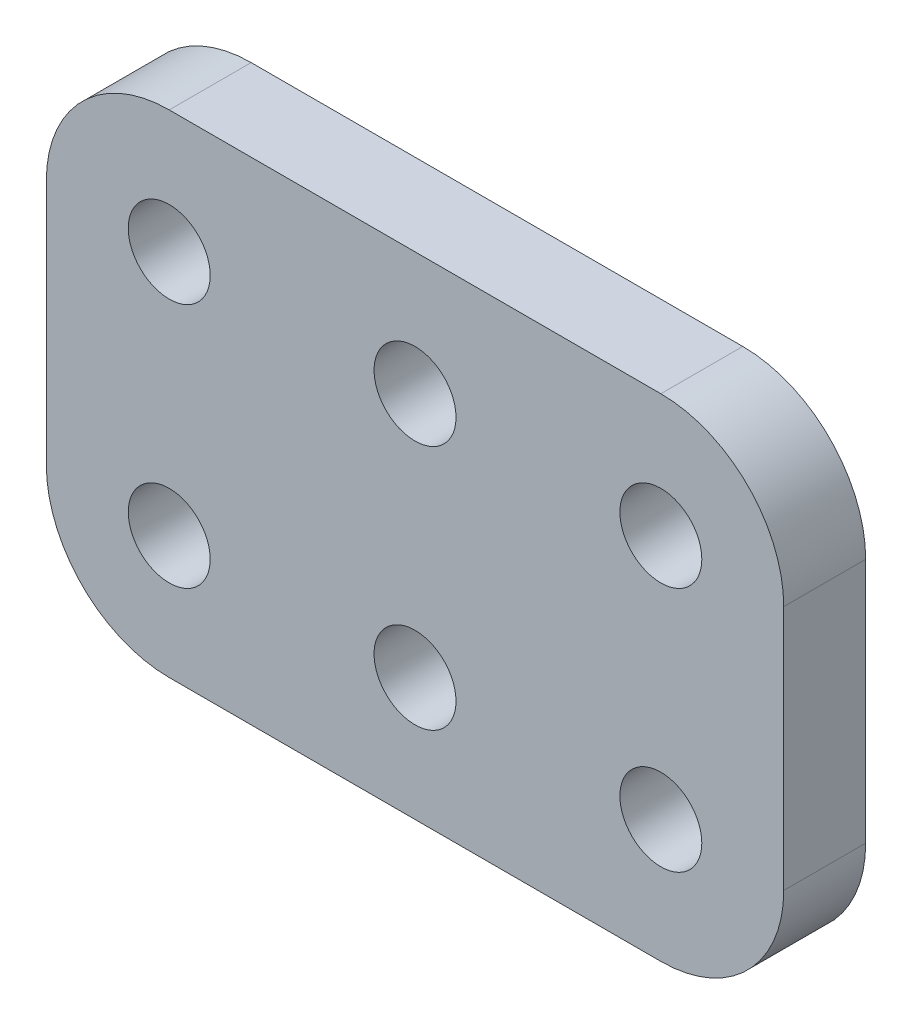
SolidWorks part; units mm, degrees
ref_plane "Alzado" through (0, 0, 0) normal (0, 0, 1) x (1, 0, 0)
ref_plane "Planta" through (0, 0, 0) normal (0, 1, 0) x (1, 0, 0)
ref_plane "Vista lateral" through (0, 0, 0) normal (1, 0, 0) x (0, 0, -1)
sketch "Model" plane through (0, 0, 0) normal (0, 0, 1) x (1, 0, 0)
  line L0 (195.3359, 161.3332) -> (213.3359, 161.3332)
  line L1 (217.8359, 165.8332) -> (217.8359, 174.8332)
  line L2 (213.3359, 179.3332) -> (195.3359, 179.3332)
  line L3 (190.8359, 174.8332) -> (190.8359, 165.8332)
  circle A0 centre (195.3359, 174.8332) radius 1.5
  circle A1 centre (195.3359, 165.8332) radius 1.5
  arc A2 (213.3359, 161.3332) -> (217.8359, 165.8332) centre (213.3359, 165.8332) ccw
  arc A3 (217.8359, 174.8332) -> (213.3359, 179.3332) centre (213.3359, 174.8332) ccw
  arc A4 (195.3359, 179.3332) -> (190.8359, 174.8332) centre (195.3359, 174.8332) ccw
  arc A5 (190.8359, 165.8332) -> (195.3359, 161.3332) centre (195.3359, 165.8332) ccw
  circle A6 centre (204.3359, 174.8332) radius 1.5
  circle A7 centre (204.3359, 165.8332) radius 1.5
  circle A8 centre (213.3359, 174.8332) radius 1.5
  circle A9 centre (213.3359, 165.8332) radius 1.5
extrude "Saliente-Extruir1" add sketch "Model" along normal blind 3
